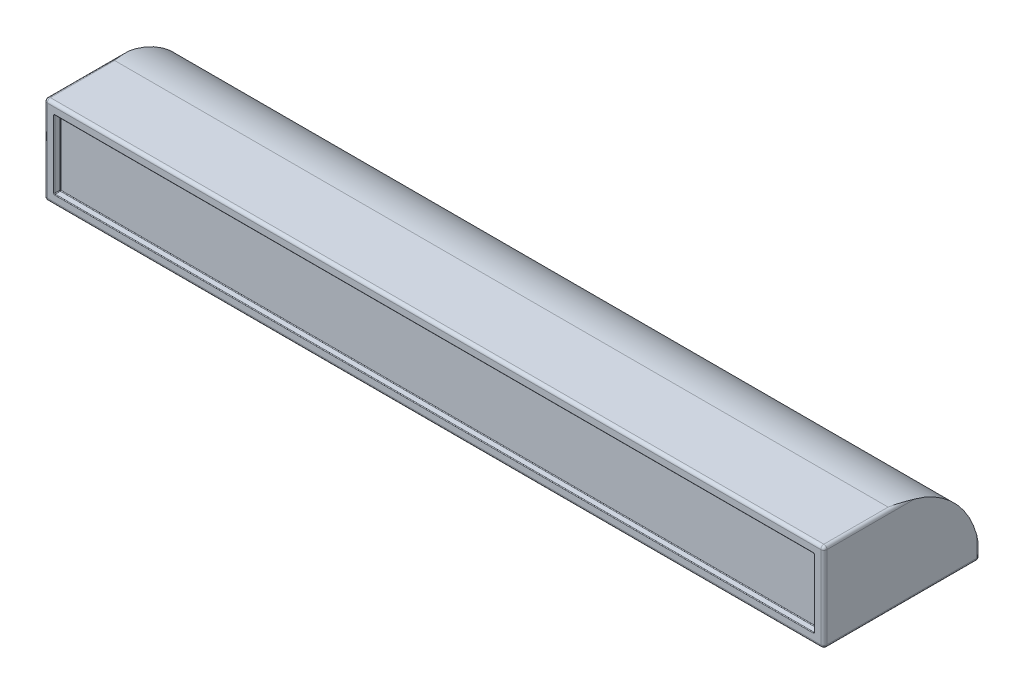
SolidWorks part; units mm, degrees
ref_plane "Front Plane" through (0, 0, 0) normal (0, 0, 1) x (1, 0, 0)
ref_plane "Top Plane" through (0, 0, 0) normal (0, 1, 0) x (1, 0, 0)
ref_plane "Right Plane" through (0, 0, 0) normal (1, 0, 0) x (0, 0, -1)
sketch "Sketch1" plane through (0, 0, 0) normal (0, 0, 1) x (1, 0, 0)
  line L1 (0, 0) -> (2500, 0)
  line L2 (0, 0) -> (0, 284)
  line L3 (0, 284) -> (2500, 284)
  line L4 (2500, 0) -> (2500, 284)
  dimension "D1" = 284
  dimension "D2" = 2500
extrude "Boss-Extrude1" add sketch "Sketch1" along normal blind 500
fillet "Fillet1" radius 10 12 edges at (2500, 142, 0) (2500, 0, 250) (1250, 0, 0) (2500, 284, 250) (1250, 284, 0) (0, 284, 250) (0, 0, 250) (0, 142, 0) (1250, 284, 500) (2500, 142, 500) (1250, 0, 500) (0, 142, 500)
sketch "Sketch2" plane through (0, 0, 500) normal (0, 0, 1) x (1, 0, 0)
  line L0 (2490, 0) -> (10, 0) construction
  line L1 (2468, 252) -> (32, 252)
  line L2 (2468, 252) -> (2468, 32)
  line L3 (2468, 32) -> (32, 32)
  line L4 (32, 252) -> (32, 32)
  line L5 (10, 284) -> (2490, 284) construction
  line L6 (2500, 274) -> (2500, 10) construction
  line L7 (0, 10) -> (0, 274) construction
  dimension "D1" = 32
  dimension "D2" = 32
  dimension "D3" = 32
  dimension "D4" = 32
extrude "Cut-Extrude1" cut sketch "Sketch2" against normal blind 20
fillet "Fillet2" radius 2 12 edges at (2468, 142, 500) (2468, 32, 490) (1250, 32, 500) (32, 32, 490) (32, 142, 500) (2468, 252, 490) (32, 252, 490) (1250, 252, 500) (1250, 32, 480) (32, 142, 480) (1250, 252, 480) (2468, 142, 480)
sketch "Sketch3" plane through (0, 0, 0) normal (-1, 0, 0) x (0, 0, 1)
  line L3 (10, 284) -> (490, 284) construction
  line L4 (0, 10) -> (0, 274) construction
  line L5 (284, 284) -> (0, 284)
  line L6 (0, 284) -> (0, 0)
  arc A1 (284, 284) -> (0, 0) centre (284, 0) ccw
  dimension "D1" = 568
extrude "Cut-Extrude2" cut sketch "Sketch3" against normal up to surface (2500 mm away) up to face at (2500, 142, 250)
